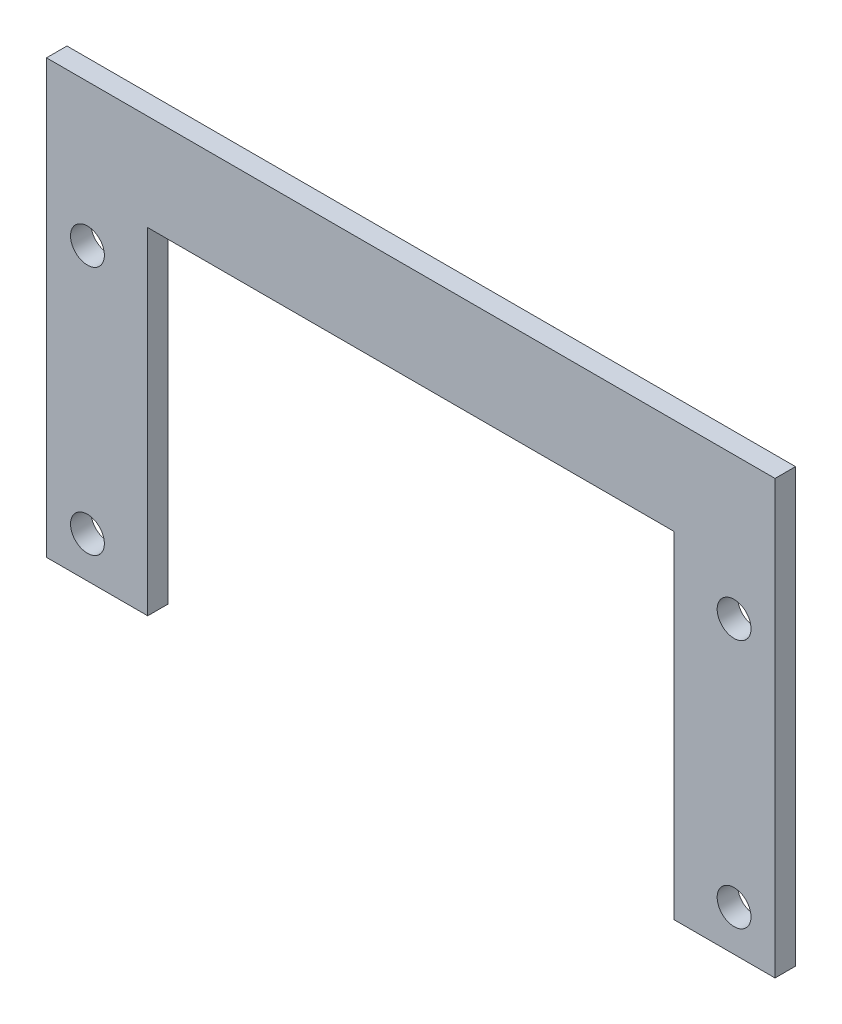
SolidWorks part; units mm, degrees
material "AISI 4130 Steel, annealed at 865C"
ref_plane "X-Y Datum" through (0, 0, 0) normal (0, 0, 1) x (1, 0, 0)
ref_plane "X-Z Datum" through (0, 0, 0) normal (0, 1, 0) x (1, 0, 0)
ref_plane "Y-Z Datum" through (0, 0, 0) normal (1, 0, 0) x (0, 0, -1)
sketch "Sketch1" plane through (0, 0, 0) normal (0, 0, 1) x (1, 0, 0)
  line L1 (-8.91, 8.69) -> (6.79, 8.69)
  line L2 (-8.91, 8.69) -> (-8.91, 75.81)
  line L3 (-8.91, 75.81) -> (6.79, 75.81)
  line L4 (6.79, 8.69) -> (6.79, 60.8535)
  line L5 (104.11, 8.69) -> (88.41, 8.69)
  line L6 (104.11, 8.69) -> (104.11, 75.81)
  line L7 (104.11, 75.81) -> (88.41, 75.81)
  line L8 (88.41, 8.69) -> (88.41, 60.8535)
  line L9 (6.79, 75.81) -> (88.41, 75.81)
  line L11 (6.79, 60.8535) -> (88.41, 60.8535)
  circle A0 centre (-2.56, 53.76) radius 2.625
  circle A1 centre (-2.56, 15.04) radius 2.625
  circle A2 centre (97.76, 15.04) radius 2.625
  circle A3 centre (97.76, 53.76) radius 2.625
extrude "Boss-Extrude1" add sketch "Sketch1" along normal blind 3.175
